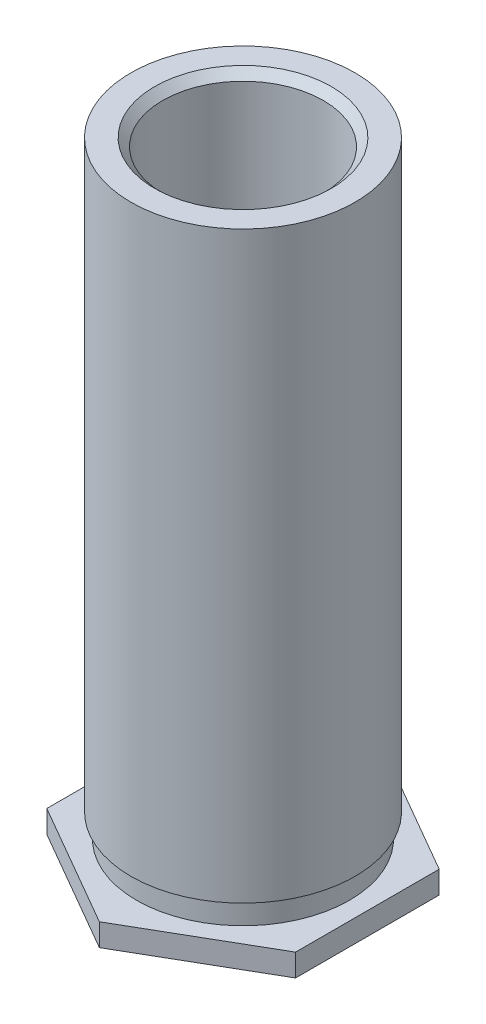
SolidWorks part; units mm, degrees
ref_plane "Plane1" through (0, 0, 0) normal (0, 0, 1) x (1, 0, 0)
ref_plane "Plane2" through (0, 0, 0) normal (0, 1, 0) x (1, 0, 0)
ref_plane "Plane3" through (0, 0, 0) normal (1, 0, 0) x (0, 0, -1)
sketch "BodySke" plane through (0, 0, 0) normal (0, 0, 1) x (1, 0, 0)
  line L0 (3.56, 0) -> (4.582, 0)
  line L1 (4.582, 0) -> (4.582, 0.712)
  line L2 (4.582, 0.712) -> (3.382, 0.712)
  line L3 (2.55, 19.745) -> (2.55, 0.2601)
  line L4 (3.56, 1.4596) -> (3.382, 1.4596)
  line L5 (3.382, 1.4596) -> (3.382, 0.712)
  line L6 (3.56, 0.0051) -> (3.56, 0)
  line L7 (2.805, 0.0051) -> (3.56, 0.0051)
  line L8 (3.56, 20) -> (2.805, 20)
  line L9 (0, 0) -> (0, 15.24) construction
  line L10 (2.805, 20) -> (2.55, 19.745)
  line L11 (3.56, 20) -> (3.56, 1.4596)
  line L12 (2.55, 0.2601) -> (2.805, 0.0051)
  dimension "E_dia" = 9.164
  dimension "C_dia" = 7.12
  dimension "Length" = 20
  dimension "Clinching_ht" = 0.712
  dimension "Groove_wid" = 0.7476
  dimension "Groove_dia" = 6.764
  dimension "Thru_dia" = 5.1
  dimension "D1" = 0.0051
  dimension "D2" = 45
  dimension "D3" = 45
  dimension "Chamfer_dia" = 5.61
revolve "Body" add sketch "BodySke" angle 360 about L9
ref_plane "Plane4" through (0, -0.5486, 0) normal (0, 1, 0) x (-1, 0, 0)
sketch "HexDieSke" plane through (0, 0.712, 0) normal (0, 1, 0) x (-1, 0, 0)
  line L0 (0, 4.5611) -> (3.95, 2.2805)
  line L1 (3.95, 2.2805) -> (3.95, -2.2805)
  line L2 (3.95, -2.2805) -> (0, -4.5611)
  line L3 (0, -4.5611) -> (-3.95, -2.2805)
  line L4 (-3.95, -2.2805) -> (-3.95, 2.2805)
  line L5 (-3.95, 2.2805) -> (0, 4.5611)
  circle A1 centre (0, 0) radius 3.95 construction
  circle A2 centre (0, 0) radius 4.5611 construction
  circle A3 centre (0, 0) radius 4.5825
  dimension "Width_across_flats" = 7.9
  dimension "OD" = 9.165
extrude "HexDie" cut sketch "HexDieSke" against normal blind 0.712
equation "' \"Length@BodySke\" = 20"
equation "' \"Thru_dia@BodySke\" = 5.1"
equation "' \"C_dia@BodySke\" = 7.12"
equation "' \"Width_across_flats@HexDieSke\" = 7.9"
equation "\"E_dia@BodySke\" = \"Width_across_flats@HexDieSke\" * 1.16"
equation "\"Chamfer_dia@BodySke\" = \"Thru_dia@BodySke\" * 1.1"
equation "\"Clinching_ht@BodySke\" = \"C_dia@BodySke\" * 0.1"
equation "\"Groove_dia@BodySke\" = \"C_dia@BodySke\" * 0.95"
equation "\"Groove_wid@BodySke\" = \"Clinching_ht@BodySke\" * 1.05"
equation "\"Depth@HexDie\" = \"Clinching_ht@BodySke\""
equation "\"OD@HexDieSke\" =  \"Width_across_flats@HexDieSke\" * 1.16 + 0.001"
